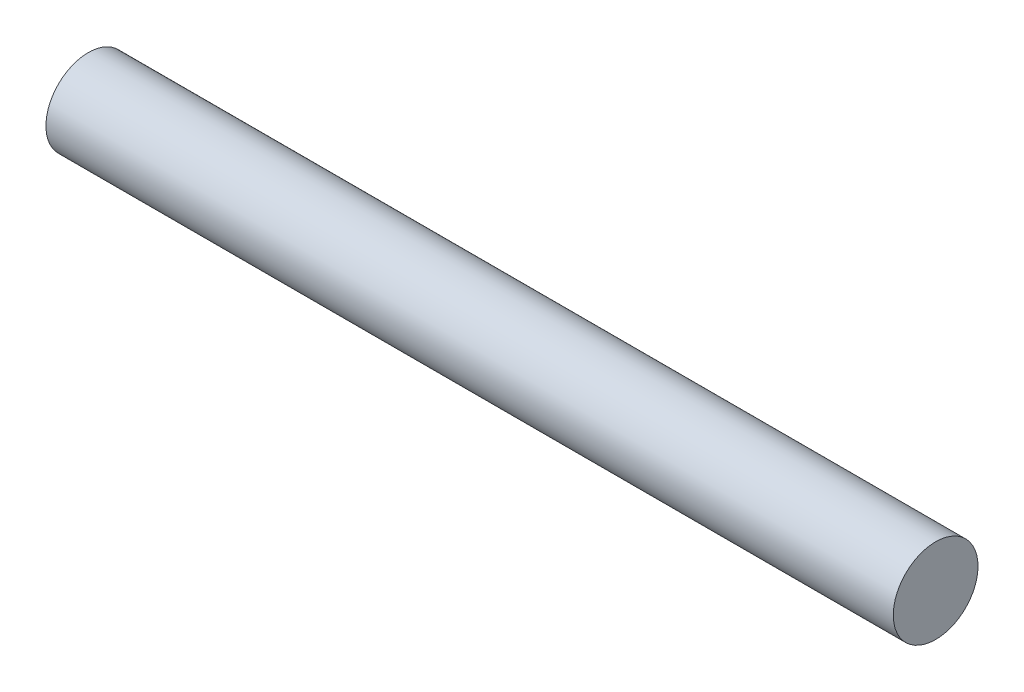
SolidWorks part; units mm, degrees
material "6061 Alloy"
ref_plane "Front Plane" through (0, 0, 0) normal (0, 0, 1) x (1, 0, 0)
ref_plane "Top Plane" through (0, 0, 0) normal (0, 1, 0) x (1, 0, 0)
ref_plane "Right Plane" through (0, 0, 0) normal (1, 0, 0) x (0, 0, -1)
sketch "Sketch2" plane through (0, 0, 0) normal (1, 0, 0) x (0, 0, -1)
  line L1 (0, 7.3323) -> (-6.35, 3.6662)
  line L2 (-6.35, 3.6662) -> (-6.35, -3.6662)
  line L3 (-6.35, -3.6662) -> (0, -7.3323)
  line L4 (0, -7.3323) -> (6.35, -3.6662)
  line L5 (6.35, -3.6662) -> (6.35, 3.6662)
  line L6 (6.35, 3.6662) -> (0, 7.3323)
  circle A0 centre (0, 0) radius 6.35 construction
  circle A1 centre (0, 0) radius 6.35
  dimension "D1" = 12.7
extrude "Boss-Extrude1" add sketch "Sketch2" along normal blind 127 contours A1
